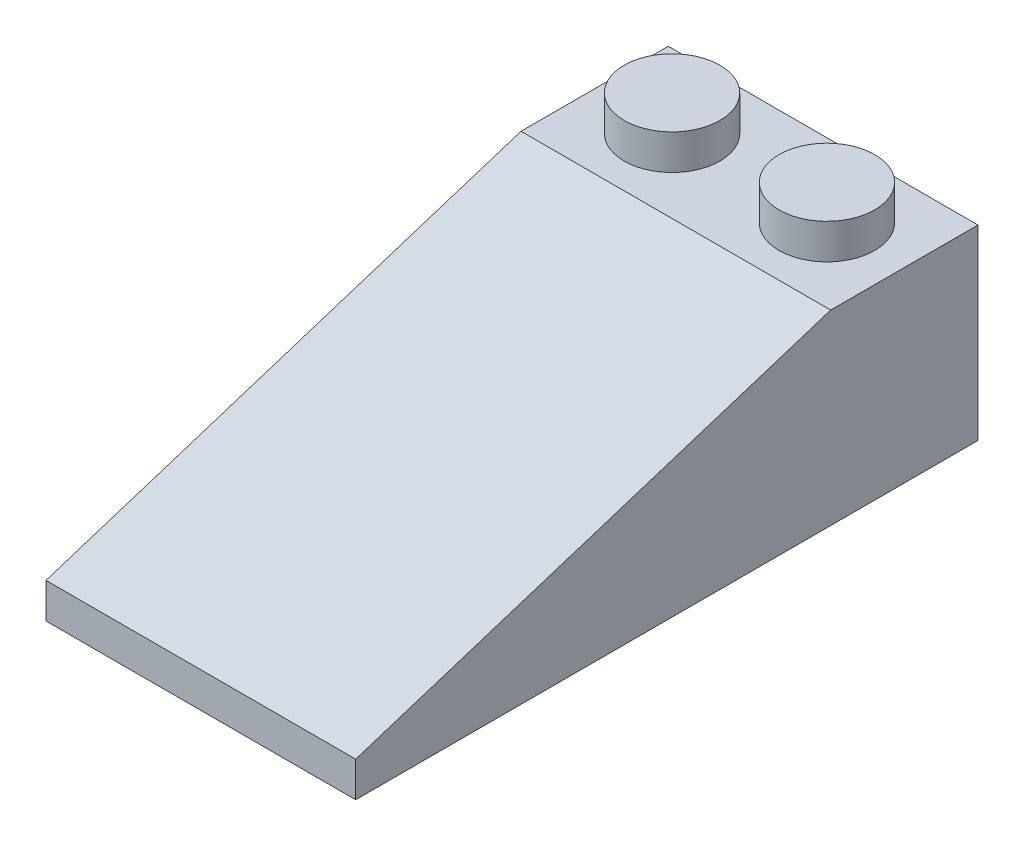
SolidWorks part; units mm, degrees
ref_plane "Front Plane" through (0, 0, 0) normal (0, 0, 1) x (1, 0, 0)
ref_plane "Top Plane" through (0, 0, 0) normal (0, 1, 0) x (1, 0, 0)
ref_plane "Right Plane" through (0, 0, 0) normal (1, 0, 0) x (0, 0, -1)
sketch "Sketch2" plane through (0, 0, 0) normal (1, 0, 0) x (0, 0, -1)
  line L0 (0, 0) -> (-31.85, 0)
  line L1 (-31.85, 0) -> (-31.85, 1.8)
  line L2 (-31.85, 1.8) -> (-7.54, 9.55)
  line L3 (-7.54, 9.55) -> (0, 9.55)
  line L4 (0, 9.55) -> (0, 0)
  dimension "D1" = 9.55
  dimension "D2" = 31.85
  dimension "D3" = 1.8
  dimension "D4" = 7.54
extrude "Boss-Extrude1" add sketch "Sketch2" against normal blind 15.85
sketch "Sketch3" plane through (0, 9.55, 0) normal (0, 1, 0) x (1, 0, 0)
  line L1 (-15.85, 0) -> (0, 0) construction
  line L2 (-15.85, 0) -> (-15.85, -7.54) construction
  circle A0 centre (-11.8875, -3.77) radius 2.45
  circle A1 centre (-3.9625, -3.77) radius 2.45
  dimension "D2" = 3.9625
  dimension "D3" = 4.9
  dimension "D5" = 7.925
  dimension "D1" = 3.77
  dimension "D4" = 2
extrude "Boss-Extrude2" add sketch "Sketch3" along normal blind 1.8
shell "Shell1" thickness 1.5
sketch "Sketch4" plane through (0, 0, 0) normal (0, 1, 0) x (1, 0, 0)
  line L1 (0, -31.85) -> (0, 0) construction
  line L2 (-15.85, -31.85) -> (0, -31.85) construction
  circle A0 centre (-7.925, -23.8875) radius 3.25
  circle A1 centre (-7.925, -23.8875) radius 2.45
  circle A2 centre (-7.925, -15.925) radius 2.45
  circle A3 centre (-7.925, -15.925) radius 3.25
  circle A4 centre (-7.925, -7.9625) radius 2.45
  circle A5 centre (-7.925, -7.9625) radius 3.25
  dimension "D3" = 6.5
  dimension "D4" = 4.9
  dimension "D6" = 7.9625
  dimension "D1" = 7.925
  dimension "D2" = 7.9625
  dimension "D5" = 3
extrude "Boss-Extrude3" add sketch "Sketch4" along normal up to surface (1.728 mm away)
